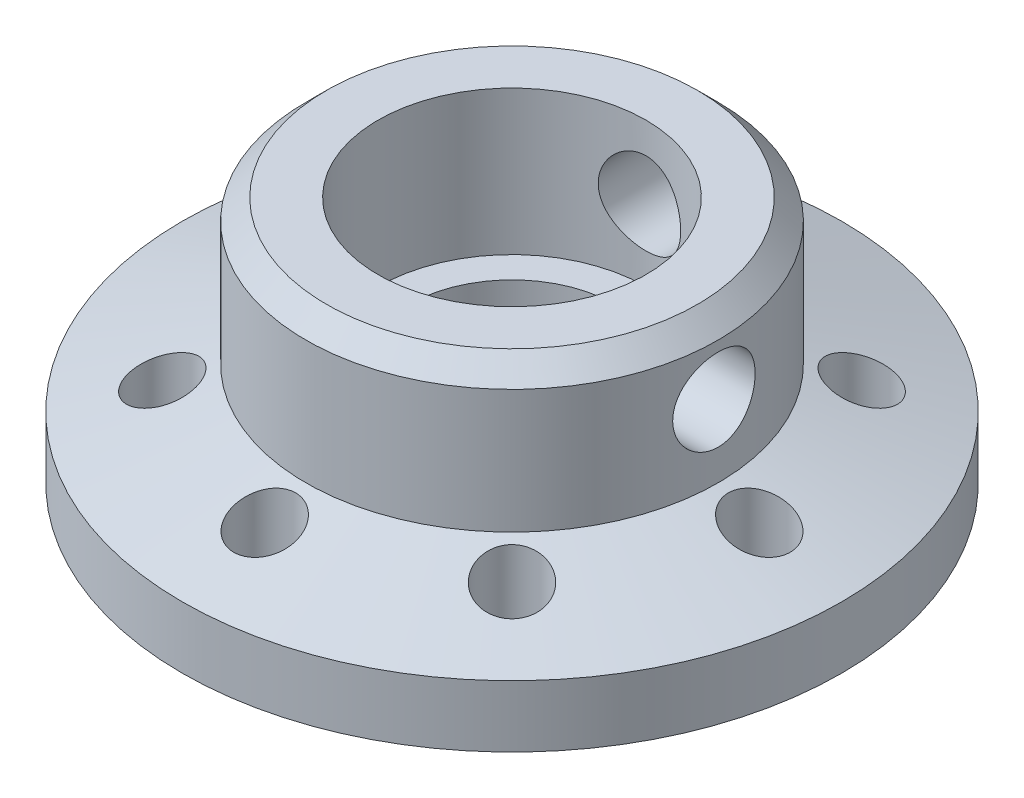
SolidWorks part; units mm, degrees
ref_plane "Front Plane" through (0, 0, 0) normal (0, 0, 1) x (1, 0, 0)
ref_plane "Top Plane" through (0, 0, 0) normal (0, 1, 0) x (1, 0, 0)
ref_plane "Right Plane" through (0, 0, 0) normal (1, 0, 0) x (0, 0, -1)
sketch "Sketch1" plane through (0, 0, 0) normal (0, 0, 1) x (1, 0, 0)
  line L0 (0, 0) -> (0, 12) construction
  line L1 (0, 12) -> (10, 12)
  line L2 (10, 12) -> (10, 5)
  line L3 (10, 5) -> (16, 3)
  line L4 (16, 3) -> (16, 0)
  line L5 (16, 0) -> (0, 0)
  line L6 (2.5, 12) -> (2.5, 0) construction
  line L7 (6.5, 12) -> (6.5, 5)
  line L8 (6.5, 5) -> (5, 5)
  line L9 (5, 5) -> (5, 0)
  dimension "D1" = 12
  dimension "D2" = 2.5
  dimension "D3" = 6.5
  dimension "D4" = 10
  dimension "D5" = 5
  dimension "D6" = 5
  dimension "D7" = 16
  dimension "D8" = 3
  dimension "D9" = 5
revolve "Revolve1" add sketch "Sketch1" angle 360 about L0
sketch "Sketch2" plane through (0, 0, 0) normal (0, -1, 0) x (1, 0, 0)
  line L0 (0, 0) -> (0, 12) construction
  circle A0 centre (0, 12) radius 1.5
  circle A1 centre (8.4853, 8.4853) radius 1.5
  circle A2 centre (12, 0) radius 1.5
  circle A3 centre (8.4853, -8.4853) radius 1.5
  circle A4 centre (0, -12) radius 1.5
  circle A5 centre (-8.4853, -8.4853) radius 1.5
  circle A6 centre (-12, 0) radius 1.5
  circle A7 centre (-8.4853, 8.4853) radius 1.5
  point P21 (0, 0)
  dimension "D1" = 3
  dimension "D2" = 12
  dimension "D3" = 8
extrude "Cut-Extrude1" cut sketch "Sketch2" against normal blind 10
sketch "Sketch3" plane through (0, 0, 0) normal (0, 0, 1) x (1, 0, 0)
  line L0 (0, 12) -> (0, 0) construction
  line L1 (10, 12) -> (-10, 12) construction
  line L2 (6.5, 12) -> (-6.5, 12) construction
  circle A0 centre (0, 8.5) radius 2
  dimension "D1" = 4
  dimension "D2" = 3.5
extrude "Cut-Extrude2" cut sketch "Sketch3" against normal through all
pattern_circular "CirPattern1" count 2 every 90 about axis through (0, 12, 0) along (0, -1, 0) of "Cut-Extrude2"
chamfer "Chamfer1" distance 1 angle 45 1 edges at (0, 12, -10)
